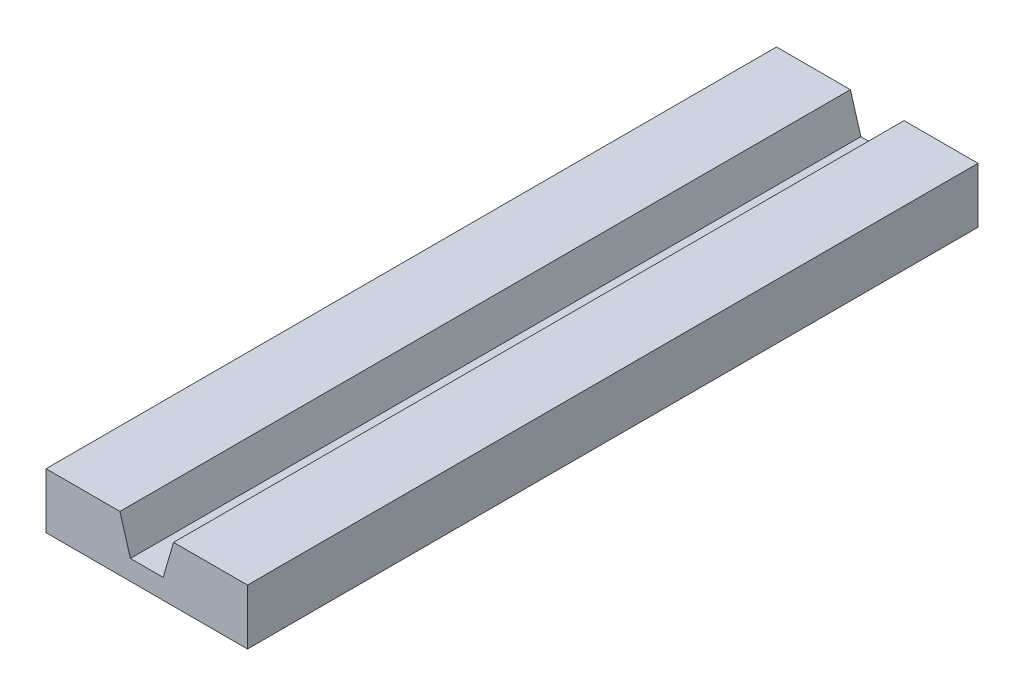
SolidWorks part; units mm, degrees
ref_plane "Alzado" through (0, 0, 0) normal (0, 0, 1) x (1, 0, 0)
ref_plane "Planta" through (0, 0, 0) normal (0, 1, 0) x (1, 0, 0)
ref_plane "Vista lateral" through (0, 0, 0) normal (1, 0, 0) x (0, 0, -1)
sketch "Croquis1" plane through (0, 0, 0) normal (0, 0, 1) x (1, 0, 0)
  line L0 (-6.5, 0) -> (6.5, 0)
  line L2 (6.5, 0) -> (10.65, 14.1)
  line L3 (-10.65, 14.1) -> (-6.5, 0)
  line L4 (-40, 14.1) -> (-10.65, 14.1)
  line L5 (10.65, 14.1) -> (40, 14.1)
  line L6 (-40, 14.1) -> (-40, -7.9)
  line L7 (-40, -7.9) -> (40, -7.9)
  line L8 (40, -7.9) -> (40, 14.1)
  point P4 (0, 0)
  dimension "D1" = 14.1
  dimension "D2" = 13
  dimension "D3" = 21.3
  dimension "D4" = 73.599
  dimension "D5" = 80
  dimension "D6" = 22
extrude "Saliente-Extruir1" add sketch "Croquis1" against normal blind 290
